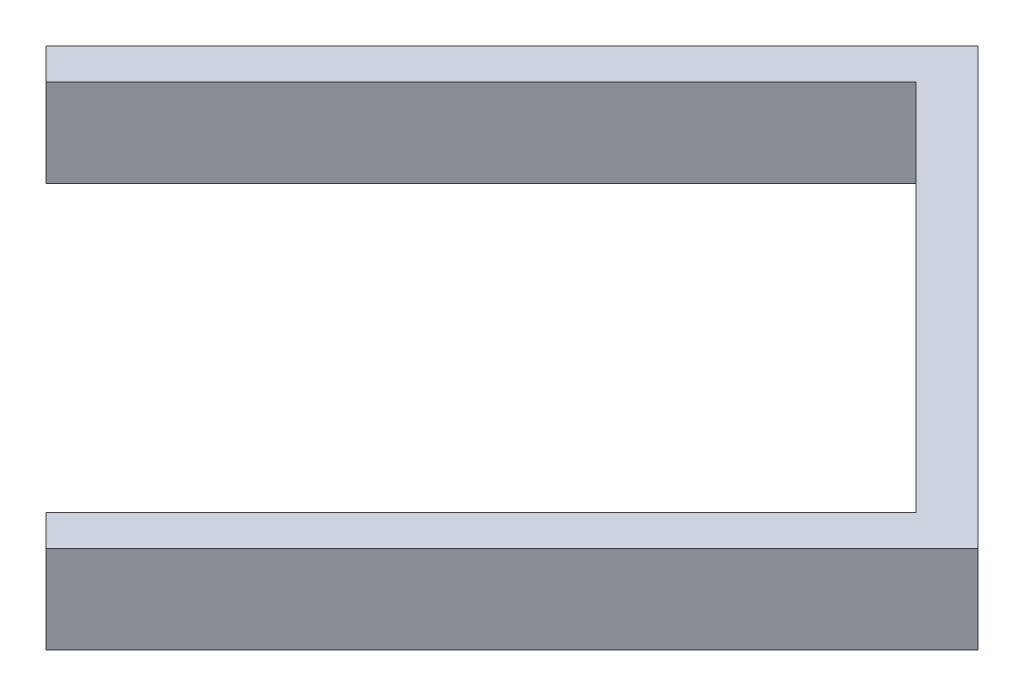
SolidWorks part; units mm, degrees
ref_plane "Front Plane" through (0, 0, 0) normal (0, 0, 1) x (1, 0, 0)
ref_plane "Top Plane" through (0, 0, 0) normal (0, 1, 0) x (1, 0, 0)
ref_plane "Right Plane" through (0, 0, 0) normal (1, 0, 0) x (0, 0, -1)
sketch "Sketch2" plane through (0, 0, 0) normal (0, 1, 0) x (1, 0, 0)
  line L0 (-240.1433, -24.0362) -> (-258.1038, -6.0757)
  line L1 (-258.1038, -6.0757) -> (11.3039, 263.332)
  line L2 (11.3039, 263.332) -> (262.7511, 11.8848)
  line L3 (262.7511, 11.8848) -> (-6.6566, -257.5229)
  line L4 (-6.6566, -257.5229) -> (-24.6171, -239.5624)
  line L5 (-24.6171, -239.5624) -> (226.83, 11.8848)
  line L6 (226.83, 11.8848) -> (11.3039, 227.4109)
  line L7 (11.3039, 227.4109) -> (-240.1433, -24.0362)
  line L8 (-118.8793, -118.2984) -> (119.067, 119.6479)
  point P10 (119.067, 119.6479)
  dimension "D1" = 25.4
  dimension "D2" = 25.4
  dimension "D3" = 304.8
  dimension "D4" = 355.6
extrude "Boss-Extrude2" add sketch "Sketch2" along normal blind 50.8 contours L7 L6 L5 L4 L3 L2 L1 L0
sketch "Sketch3" plane through (137.3179, 0, -137.3179) normal (0.7071, 0, -0.7071) x (-0.7071, 0, -0.7071)
  line L0 (178.2108, 50.8) -> (178.2108, 0) construction
  circle A0 centre (0, 25.4) radius 6.35
  point P5 (178.2108, 25.4)
  dimension "D1" = 12.7
extrude "Cut-Extrude1" cut sketch "Sketch3" against normal blind 50.8
